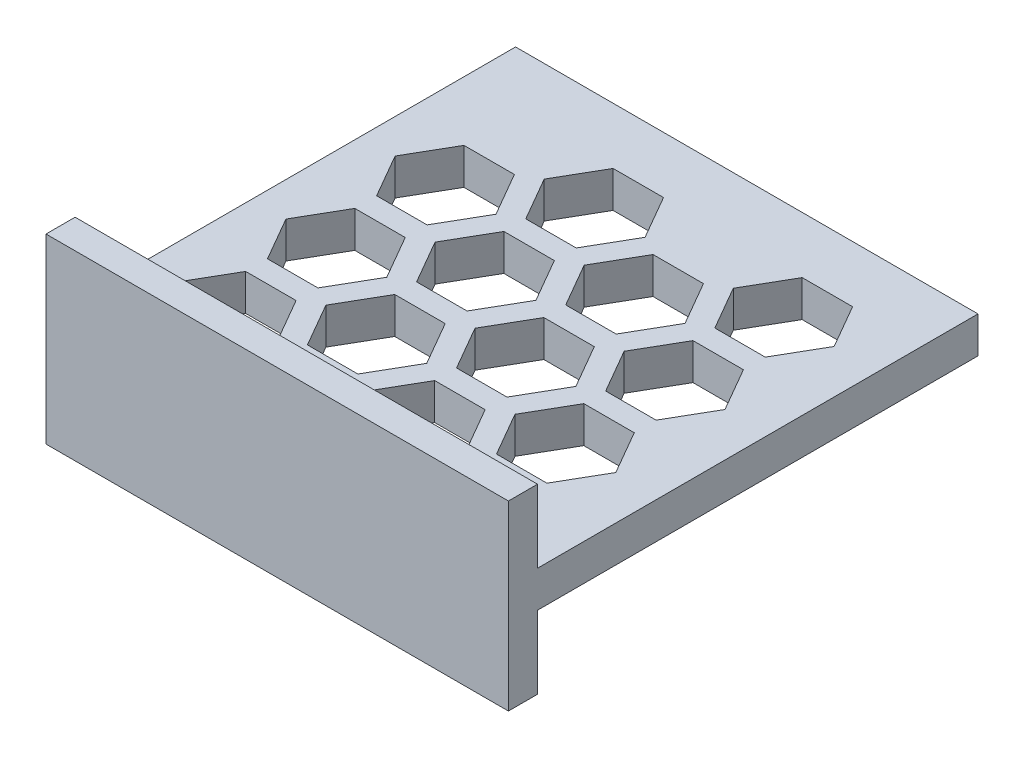
SolidWorks part; units mm, degrees
ref_plane "Front Plane" through (0, 0, 0) normal (0, 0, 1) x (1, 0, 0)
ref_plane "Top Plane" through (0, 0, 0) normal (0, 1, 0) x (1, 0, 0)
ref_plane "Right Plane" through (0, 0, 0) normal (1, 0, 0) x (0, 0, -1)
sketch "Sketch1" plane through (0, 0, 0) normal (0, 1, 0) x (1, 0, 0)
  line L0 (5.8158, 4.6333) -> (12.311, 8.3833) construction
  line L1 (0, 0) -> (31.7704, 0)
  line L2 (0, 0) -> (0, 30.2628)
  line L3 (0, 30.2628) -> (31.7704, 30.2628)
  line L4 (31.7704, 0) -> (31.7704, 30.2628)
  line L5 (7.5478, 7.6333) -> (4.0837, 7.6333)
  line L6 (4.0837, 7.6333) -> (2.3517, 4.6333)
  line L7 (2.3517, 4.6333) -> (4.0837, 1.6333)
  line L8 (4.0837, 1.6333) -> (7.5478, 1.6333)
  line L9 (7.5478, 1.6333) -> (9.2799, 4.6333)
  line L10 (9.2799, 4.6333) -> (7.5478, 7.6333)
  line L11 (14.043, 11.3833) -> (10.5789, 11.3833)
  line L12 (10.5789, 11.3833) -> (8.8469, 8.3833)
  line L13 (8.8469, 8.3833) -> (10.5789, 5.3833)
  line L14 (10.5789, 5.3833) -> (14.043, 5.3833)
  line L15 (14.043, 5.3833) -> (15.7751, 8.3833)
  line L16 (15.7751, 8.3833) -> (14.043, 11.3833)
  line L17 (20.5378, 7.6333) -> (17.0737, 7.6333)
  line L18 (17.0737, 7.6333) -> (15.3417, 4.6333)
  line L19 (15.3417, 4.6333) -> (17.0737, 1.6333)
  line L20 (17.0737, 1.6333) -> (20.5378, 1.6333)
  line L21 (20.5378, 1.6333) -> (22.2699, 4.6333)
  line L22 (22.2699, 4.6333) -> (20.5378, 7.6333)
  line L23 (27.033, 11.3833) -> (23.5689, 11.3833)
  line L24 (23.5689, 11.3833) -> (21.8369, 8.3833)
  line L25 (21.8369, 8.3833) -> (23.5689, 5.3833)
  line L26 (23.5689, 5.3833) -> (27.033, 5.3833)
  line L27 (27.033, 5.3833) -> (28.7651, 8.3833)
  line L28 (28.7651, 8.3833) -> (27.033, 11.3833)
  line L29 (20.5378, 15.1333) -> (17.0737, 15.1333)
  line L30 (17.0737, 15.1333) -> (15.3417, 12.1333)
  line L31 (15.3417, 12.1333) -> (17.0737, 9.1333)
  line L32 (17.0737, 9.1333) -> (20.5378, 9.1333)
  line L33 (20.5378, 9.1333) -> (22.2699, 12.1333)
  line L34 (22.2699, 12.1333) -> (20.5378, 15.1333)
  line L35 (27.033, 18.8833) -> (23.5689, 18.8833)
  line L36 (23.5689, 18.8833) -> (21.8369, 15.8833)
  line L37 (21.8369, 15.8833) -> (23.5689, 12.8833)
  line L38 (23.5689, 12.8833) -> (27.033, 12.8833)
  line L39 (27.033, 12.8833) -> (28.7651, 15.8833)
  line L40 (28.7651, 15.8833) -> (27.033, 18.8833)
  line L41 (20.5378, 22.6333) -> (17.0737, 22.6333)
  line L42 (17.0737, 22.6333) -> (15.3417, 19.6333)
  line L43 (15.3417, 19.6333) -> (17.0737, 16.6333)
  line L44 (17.0737, 16.6333) -> (20.5378, 16.6333)
  line L45 (20.5378, 16.6333) -> (22.2699, 19.6333)
  line L46 (22.2699, 19.6333) -> (20.5378, 22.6333)
  line L47 (27.033, 26.3833) -> (23.5689, 26.3833)
  line L48 (23.5689, 26.3833) -> (21.8369, 23.3833)
  line L49 (21.8369, 23.3833) -> (23.5689, 20.3833)
  line L50 (23.5689, 20.3833) -> (27.033, 20.3833)
  line L51 (27.033, 20.3833) -> (28.7651, 23.3833)
  line L52 (28.7651, 23.3833) -> (27.033, 26.3833)
  line L53 (7.5478, 15.1333) -> (4.0837, 15.1333)
  line L54 (4.0837, 15.1333) -> (2.3517, 12.1333)
  line L55 (2.3517, 12.1333) -> (4.0837, 9.1333)
  line L56 (4.0837, 9.1333) -> (7.5478, 9.1333)
  line L57 (7.5478, 9.1333) -> (9.2799, 12.1333)
  line L58 (9.2799, 12.1333) -> (7.5478, 15.1333)
  line L59 (14.043, 18.8833) -> (10.5789, 18.8833)
  line L60 (10.5789, 18.8833) -> (8.8469, 15.8833)
  line L61 (8.8469, 15.8833) -> (10.5789, 12.8833)
  line L62 (10.5789, 12.8833) -> (14.043, 12.8833)
  line L63 (14.043, 12.8833) -> (15.7751, 15.8833)
  line L64 (15.7751, 15.8833) -> (14.043, 18.8833)
  line L65 (7.5478, 22.6333) -> (4.0837, 22.6333)
  line L66 (4.0837, 22.6333) -> (2.3517, 19.6333)
  line L67 (2.3517, 19.6333) -> (4.0837, 16.6333)
  line L68 (4.0837, 16.6333) -> (7.5478, 16.6333)
  line L69 (7.5478, 16.6333) -> (9.2799, 19.6333)
  line L70 (9.2799, 19.6333) -> (7.5478, 22.6333)
  line L71 (14.043, 26.3833) -> (10.5789, 26.3833)
  line L72 (10.5789, 26.3833) -> (8.8469, 23.3833)
  line L73 (8.8469, 23.3833) -> (10.5789, 20.3833)
  line L74 (10.5789, 20.3833) -> (14.043, 20.3833)
  line L75 (14.043, 20.3833) -> (15.7751, 23.3833)
  line L76 (15.7751, 23.3833) -> (14.043, 26.3833)
  circle A0 centre (5.8158, 4.6333) radius 3 construction
  circle A1 centre (12.311, 8.3833) radius 3 construction
  dimension "D1" = 3
  dimension "D2" = 3
  dimension "D3" = 7.5
  dimension "D4" = 2
  dimension "D5" = 3
extrude "Boss-Extrude1" add sketch "Sketch1" along normal blind 2.5
sketch "Sketch2" plane through (0, 0, 0) normal (0, 0, 1) x (1, 0, 0)
  line L0 (0, 2.5) -> (31.7704, 2.5) construction
  line L1 (0, 7.5) -> (31.7704, 7.5)
  line L2 (0, 7.5) -> (0, -5)
  line L3 (0, -5) -> (31.7704, -5)
  line L4 (31.7704, 7.5) -> (31.7704, -5)
  line L5 (0, 0) -> (31.7704, 0) construction
  line L6 (31.7704, 2.5) -> (31.7704, 0) construction
  dimension "D1" = 5
  dimension "D2" = 5
  dimension "D3" = 0
extrude "Boss-Extrude2" add sketch "Sketch2" along normal blind 2
